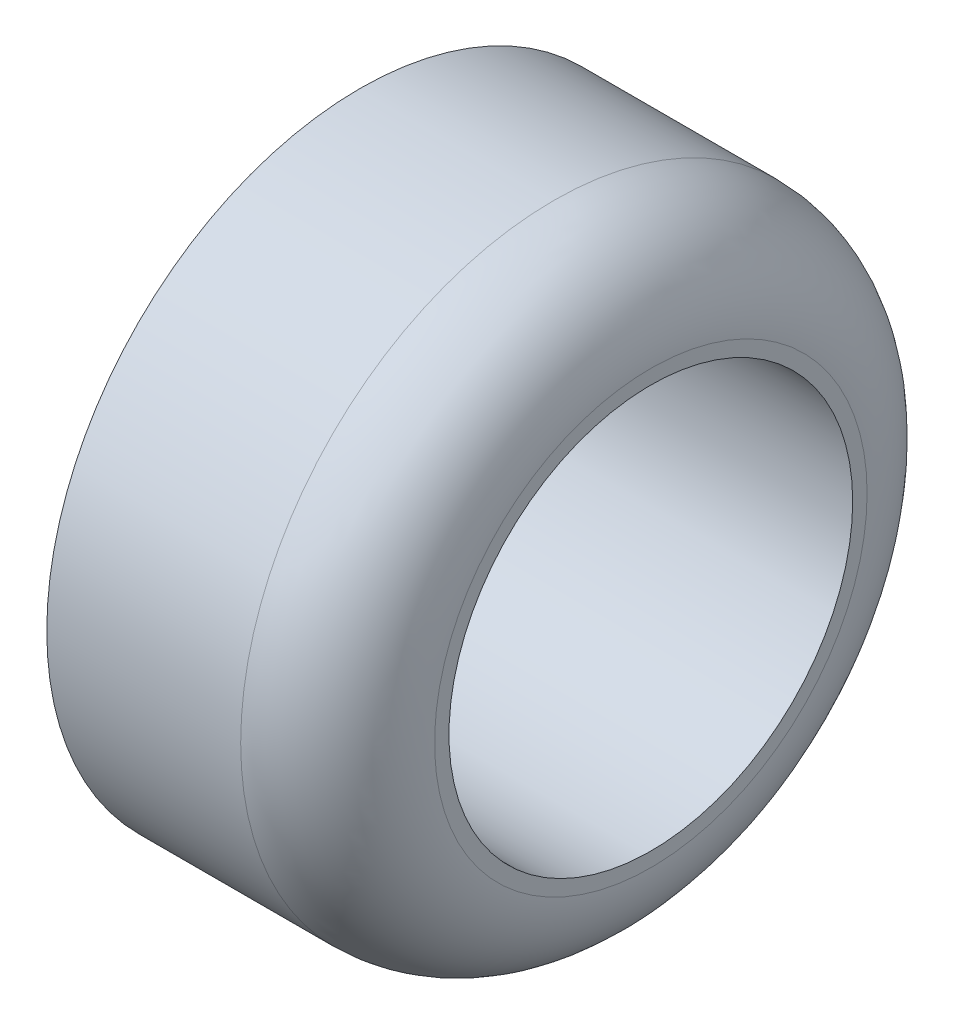
SolidWorks part; units mm, degrees
material "Rubber"
ref_plane "Front Plane" through (0, 0, 0) normal (0, 0, 1) x (1, 0, 0)
ref_plane "Top Plane" through (0, 0, 0) normal (0, 1, 0) x (1, 0, 0)
ref_plane "Right Plane" through (0, 0, 0) normal (1, 0, 0) x (0, 0, -1)
sketch "Sketch2" plane through (0, 0, 0) normal (1, 0, 0) x (0, 0, -1)
  circle A0 centre (0, 0) radius 4.2672
  circle A1 centre (0, 0) radius 2.7501
  dimension "D1" = 8.5344
  dimension "D2" = 5.5001
extrude "Boss-Extrude1" add sketch "Sketch2" against normal blind 3.9624
fillet "Fillet2" radius 1.3208 1 edges at (0, 0, -4.2672)
